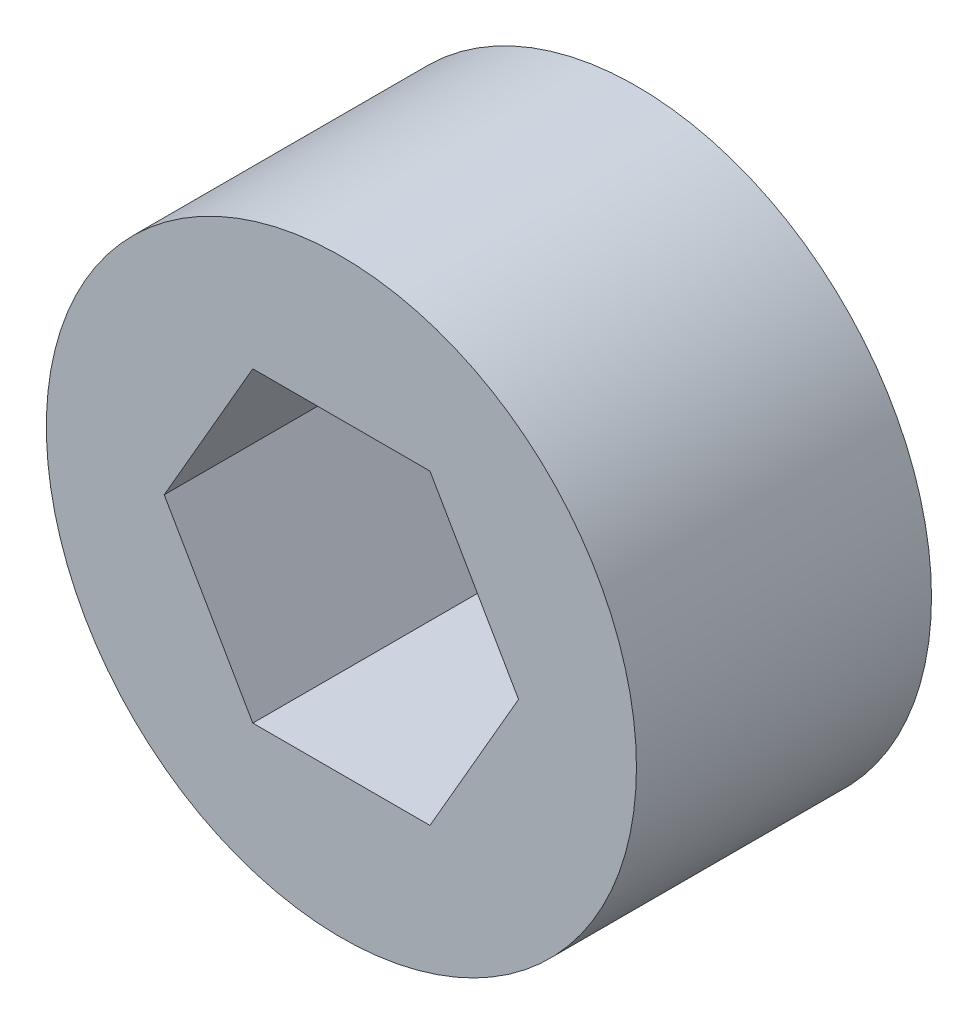
SolidWorks part; units mm, degrees
ref_plane "Front Plane" through (0, 0, 0) normal (0, 0, 1) x (1, 0, 0)
ref_plane "Top Plane" through (0, 0, 0) normal (0, 1, 0) x (1, 0, 0)
ref_plane "Right Plane" through (0, 0, 0) normal (1, 0, 0) x (0, 0, -1)
sketch "Sketch1" plane through (0, 0, 0) normal (0, 0, 1) x (1, 0, 0)
  line L1 (3.8128, -6.604) -> (7.6256, 0)
  line L2 (7.6256, 0) -> (3.8128, 6.604)
  line L3 (3.8128, 6.604) -> (-3.8128, 6.604)
  line L4 (-3.8128, 6.604) -> (-7.6256, 0)
  line L5 (-7.6256, 0) -> (-3.8128, -6.604)
  line L6 (-3.8128, -6.604) -> (3.8128, -6.604)
  circle A0 centre (0, 0) radius 6.604 construction
  circle A1 centre (0, 0) radius 12.7
  dimension "D2" = 25.4
  dimension "D1" = 13.208
extrude "Boss-Extrude1" add sketch "Sketch1" along normal blind 12.7
